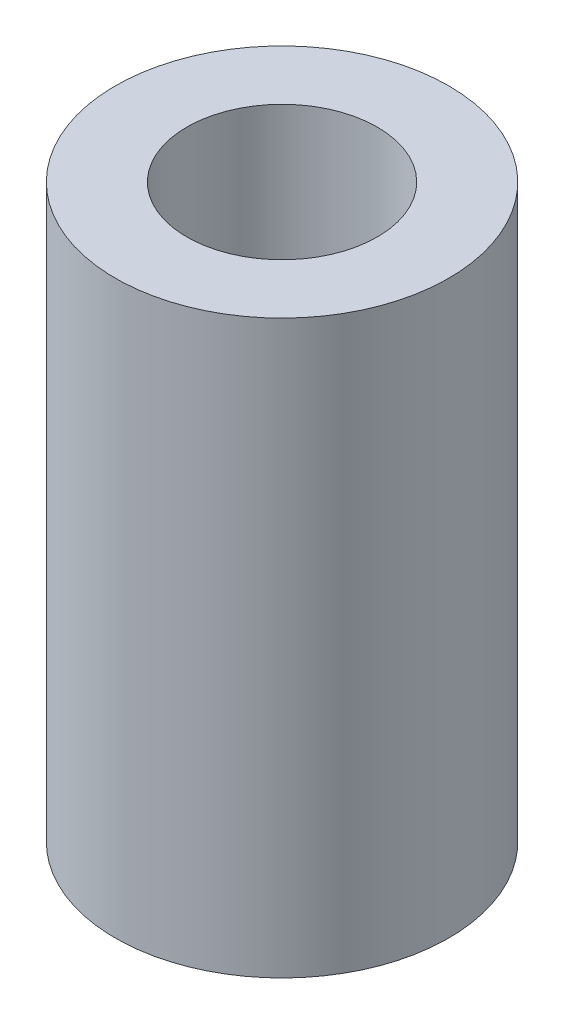
SolidWorks part; units mm, degrees
ref_plane "Front Plane" through (0, 0, 0) normal (0, 0, 1) x (1, 0, 0)
ref_plane "Top Plane" through (0, 0, 0) normal (0, 1, 0) x (1, 0, 0)
ref_plane "Right Plane" through (0, 0, 0) normal (1, 0, 0) x (0, 0, -1)
sketch "Sketch1" plane through (0, 0, 0) normal (0, 1, 0) x (1, 0, 0)
  circle A0 centre (0, 0) radius 22.225
  circle A1 centre (0, 0) radius 12.7
  dimension "D1" = 44.45
  dimension "D2" = 25.4
extrude "Boss-Extrude1" add sketch "Sketch1" along normal blind 76.2
